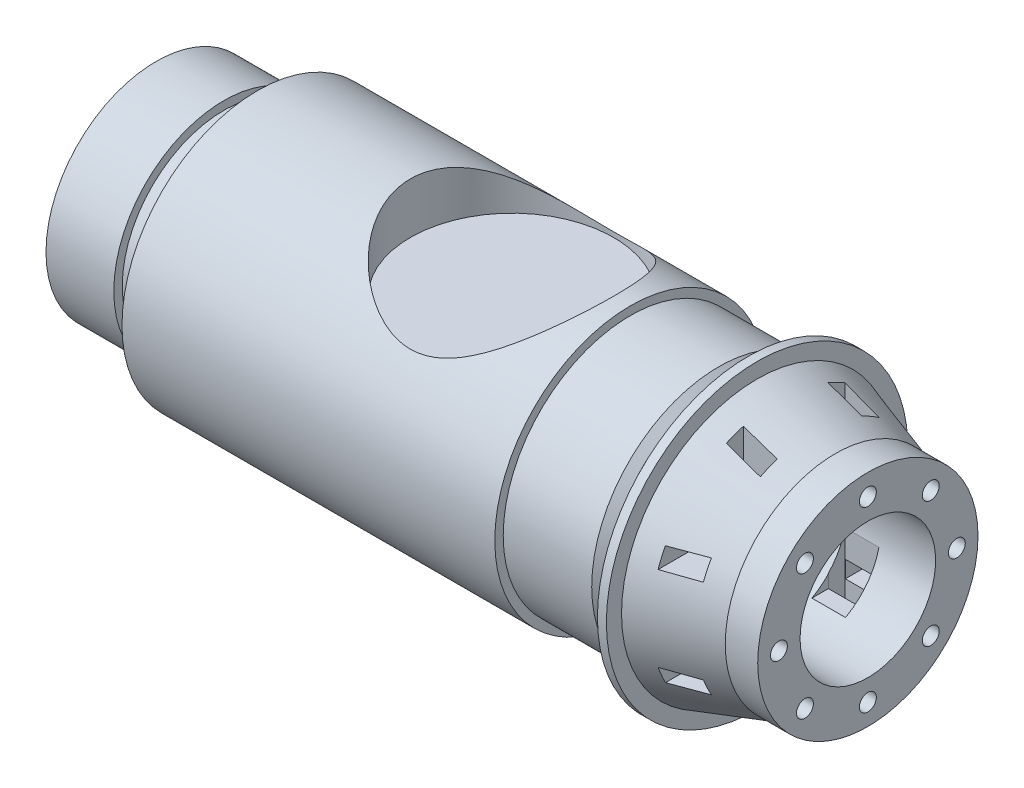
SolidWorks part; units mm, degrees
material "1060 Alloy"
ref_plane "Front Plane" through (0, 0, 0) normal (0, 0, 1) x (1, 0, 0)
ref_plane "Top Plane" through (0, 0, 0) normal (0, 1, 0) x (1, 0, 0)
ref_plane "Right Plane" through (0, 0, 0) normal (1, 0, 0) x (0, 0, -1)
sketch "Sketch2" plane through (0, 0, 0) normal (0, 1, 0) x (1, 0, 0)
  line L0 (-266.7, 0) -> (266.7, 0) construction
  line L1 (-266.7, 0) -> (-266.7, 82.55)
  line L2 (-266.7, 82.55) -> (-215.9, 82.55)
  line L3 (-215.9, 82.55) -> (-215.9, 0)
  line L4 (-215.9, 76.2) -> (-190.6964, 76.2)
  line L5 (-190.6964, 76.2) -> (-190.6964, 0)
  line L6 (-190.6964, 76.2) -> (-190.6964, 101.6)
  line L7 (-190.6964, 101.6) -> (88.7036, 101.6)
  line L8 (88.7036, 101.6) -> (88.7036, 0)
  line L9 (88.7036, 95.279) -> (155.0155, 95.279)
  line L10 (155.0155, 95.279) -> (155.0155, 0)
  line L11 (155.0155, 95.279) -> (160.5132, 89.7812)
  line L12 (160.5132, 89.7812) -> (166.011, 95.279)
  line L13 (166.011, 95.279) -> (166.011, 0)
  line L14 (177.0065, 95.279) -> (177.0065, 112.9924)
  line L15 (166.011, 95.279) -> (171.5087, 89.7812)
  line L16 (171.5087, 89.7812) -> (177.0065, 95.279)
  line L17 (177.0065, 95.279) -> (177.0065, 0)
  line L18 (177.0065, 112.9924) -> (183.7244, 112.9924)
  line L19 (183.7244, 112.9924) -> (183.7244, 0)
  line L20 (183.7244, 101.629) -> (242.3641, 82.55)
  line L21 (242.3641, 82.55) -> (266.7, 82.55)
  line L22 (266.7, 82.55) -> (266.7, 0)
  dimension "D1" = 533.4
  dimension "D2" = 82.55
  dimension "D3" = 50.8
  dimension "D4" = 76.2
  dimension "D5" = 25.4
  dimension "D6" = 279.4
  dimension "D7" = 82.55
revolve "Revolve1" add sketch "Sketch2" angle 360 about L0
ref_plane "Plane1" through (0, 121.92, 0) normal (0, 1, 0) x (1, 0, 0)
sketch "Sketch3" plane through (0, 121.92, 0) normal (0, 1, 0) x (1, 0, 0)
  line L1 (200.1242, 36.7909) -> (225.5242, 36.7909)
  line L2 (200.1242, 36.7909) -> (200.1242, 49.4909)
  line L3 (200.1242, 49.4909) -> (225.5242, 49.4909)
  line L4 (225.5242, 36.7909) -> (225.5242, 49.4909)
  line L5 (200.1242, -39.4091) -> (225.5242, -39.4091)
  line L6 (200.1242, -39.4091) -> (200.1242, -26.7091)
  line L7 (200.1242, -26.7091) -> (225.5242, -26.7091)
  line L8 (225.5242, -39.4091) -> (225.5242, -26.7091)
  dimension "D1" = 25.4
  dimension "D2" = 12.7
  dimension "D3" = 12.7
  dimension "D4" = 25.4
  dimension "D5" = 63.5
extrude "Cut-Extrude1" cut sketch "Sketch3" against normal through all
ref_plane "Plane2" through (0, 0, -121.92) normal (0, 0, 1) x (1, 0, 0)
sketch "Sketch4" plane through (0, 0, 39.4091) normal (0, 0, -1) x (-1, 0, 0)
  line L1 (-200.3273, 44.3652) -> (-225.7273, 44.3652)
  line L2 (-200.3273, 44.3652) -> (-200.3273, 31.6652)
  line L3 (-200.3273, 31.6652) -> (-225.7273, 31.6652)
  line L4 (-225.7273, 44.3652) -> (-225.7273, 31.6652)
  line L5 (-200.3273, -31.8348) -> (-225.7273, -31.8348)
  line L6 (-200.3273, -31.8348) -> (-200.3273, -44.5348)
  line L7 (-200.3273, -44.5348) -> (-225.7273, -44.5348)
  line L8 (-225.7273, -31.8348) -> (-225.7273, -44.5348)
  line M10 (-225.5242, 78.7149) -> (-225.5242, -78.7149)
  dimension "D1" = 63.5
  dimension "D2" = 25.4
  dimension "D3" = 12.7
  dimension "D4" = 12.7
  dimension "D5" = 25.4
extrude "Cut-Extrude2" cut sketch "Sketch4" against normal through all and the other way through all contours L3 L2 L1 M10 | L7 L6 L5 M10
sketch "Sketch5" plane through (-266.7, 0, 0) normal (-1, 0, 0) x (0, 0, 1)
  circle A0 centre (0, 0) radius 50.8
  dimension "D1" = 101.6
extrude "Cut-Extrude3" cut sketch "Sketch5" against normal through all
sketch "Sketch6" plane through (-266.7, 0, 0) normal (-1, 0, 0) x (0, 0, 1)
  circle A0 centre (0, 0) radius 66.675 construction
  circle A1 centre (0, 66.675) radius 6.35
  circle A2 centre (0, 0) radius 66.675 construction
  circle A3 centre (47.1463, 47.1463) radius 6.35
  circle A4 centre (0, 0) radius 66.675 construction
  circle A5 centre (66.675, 0) radius 6.35
  circle A6 centre (0, 0) radius 66.675 construction
  circle A7 centre (47.1463, -47.1463) radius 6.35
  circle A8 centre (0, 0) radius 66.675 construction
  circle A9 centre (0, -66.675) radius 6.35
  circle A10 centre (0, 0) radius 66.675 construction
  circle A11 centre (-47.1463, -47.1463) radius 6.35
  circle A12 centre (0, 0) radius 66.675 construction
  circle A13 centre (-66.675, 0) radius 6.35
  circle A14 centre (0, 0) radius 66.675 construction
  circle A15 centre (-47.1463, 47.1463) radius 6.35
  point P28 (0, 0)
  dimension "D1" = 133.35
  dimension "D2" = 12.7
  dimension "D3" = 8
extrude "Cut-Extrude4" cut sketch "Sketch6" against normal blind 25.4
sketch "Sketch7" plane through (266.7, 0, 0) normal (1, 0, 0) x (0, 0, -1)
  circle A0 centre (0, 0) radius 66.675 construction
  circle A1 centre (0, 66.675) radius 6.35
  circle A2 centre (0, 0) radius 66.675 construction
  circle A3 centre (47.1463, 47.1463) radius 6.35
  circle A4 centre (0, 0) radius 66.675 construction
  circle A5 centre (66.675, 0) radius 6.35
  circle A6 centre (0, 0) radius 66.675 construction
  circle A7 centre (47.1463, -47.1463) radius 6.35
  circle A8 centre (0, 0) radius 66.675 construction
  circle A9 centre (0, -66.675) radius 6.35
  circle A10 centre (0, 0) radius 66.675 construction
  circle A11 centre (-47.1463, -47.1463) radius 6.35
  circle A12 centre (0, 0) radius 66.675 construction
  circle A13 centre (-66.675, 0) radius 6.35
  circle A14 centre (0, 0) radius 66.675 construction
  circle A15 centre (-47.1463, 47.1463) radius 6.35
  point P28 (0, 0)
  dimension "D1" = 133.35
  dimension "D2" = 12.7
  dimension "D3" = 8
extrude "Cut-Extrude5" cut sketch "Sketch7" against normal blind 25.4
ref_plane "Plane3" through (0, 101.6, 0) normal (0, 1, 0) x (1, 0, 0)
sketch "Sketch8" plane through (0, 101.6, 0) normal (0, 1, 0) x (1, 0, 0)
  circle A0 centre (0, 0) radius 76.2
  dimension "D1" = 152.4
extrude "Cut-Extrude8" cut sketch "Sketch8" against normal blind 38.1
